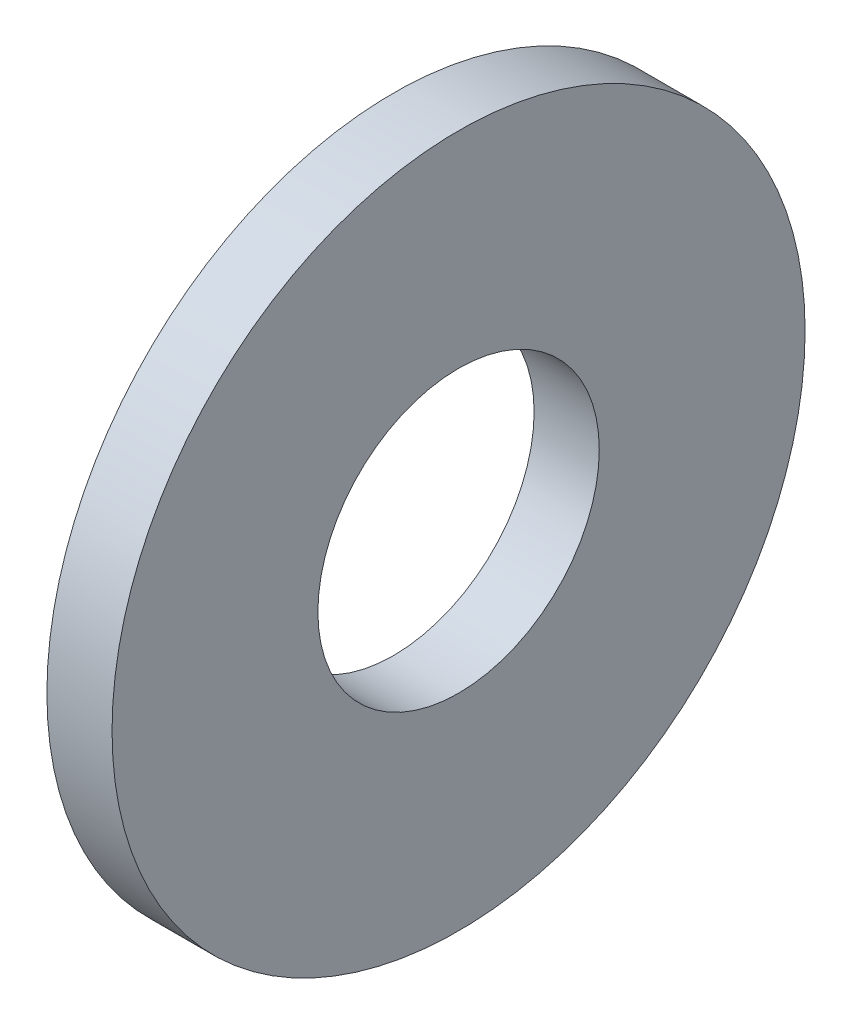
SolidWorks part; units mm, degrees
ref_plane "Front Plane" through (0, 0, 0) normal (0, 0, 1) x (1, 0, 0)
ref_plane "Top Plane" through (0, 0, 0) normal (0, 1, 0) x (1, 0, 0)
ref_plane "Right Plane" through (0, 0, 0) normal (1, 0, 0) x (0, 0, -1)
sketch "Sketch1" plane through (0, 0, 0) normal (1, 0, 0) x (0, 0, -1)
  circle A0 centre (0, 0) radius 6.35
  circle A1 centre (0, 0) radius 2.5781
  dimension "OD" = 12.7
  dimension "ID" = 5.1562
extrude "Boss-Extrude1" add sketch "Sketch1" along normal blind 1.1938
